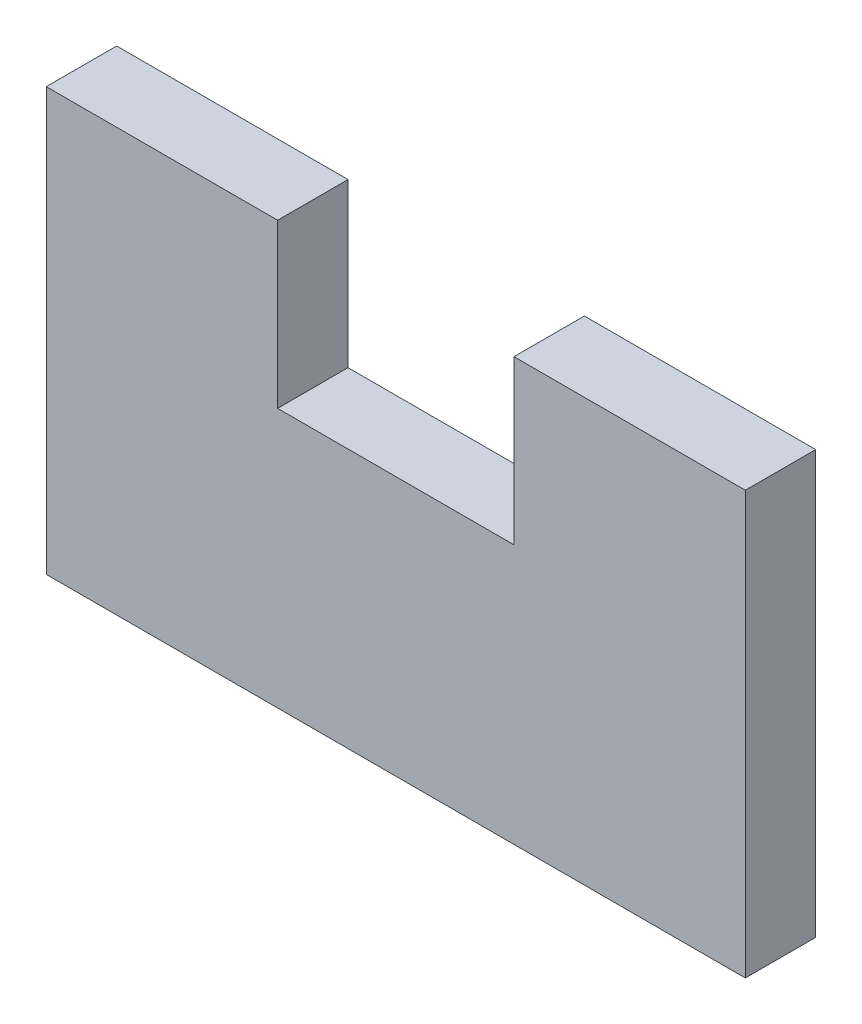
SolidWorks part; units mm, degrees
ref_plane "Front Plane" through (0, 0, 0) normal (0, 0, 1) x (1, 0, 0)
ref_plane "Top Plane" through (0, 0, 0) normal (0, 1, 0) x (1, 0, 0)
ref_plane "Right Plane" through (0, 0, 0) normal (1, 0, 0) x (0, 0, -1)
sketch "Sketch1" plane through (0, 0, 0) normal (0, 0, 1) x (1, 0, 0)
  line L0 (38.1765, 19.1703) -> (61.1765, 19.1703)
  line L1 (61.1765, 19.1703) -> (61.1765, -22.8297)
  line L2 (61.1765, -22.8297) -> (-8.3235, -22.8297)
  line L3 (-8.3235, -22.8297) -> (-8.3235, 19.1703)
  line L4 (-8.3235, 19.1703) -> (14.6765, 19.1703)
  line L6 (14.6765, 19.1703) -> (14.6765, 2.9703)
  line L7 (14.6765, 2.9703) -> (38.1765, 2.9703)
  line L8 (38.1765, 2.9703) -> (38.1765, 19.1703)
  dimension "D1" = 23
  dimension "D2" = 23
  dimension "D3" = 23.5
  dimension "D4" = 16.2
  dimension "D5" = 42
extrude "Boss-Extrude1" add sketch "Sketch1" along normal blind 7 contours L2 L3 L4 L6 L7 L8 L0 L1
sketch "Sketch2" plane through (0, 0, 7) normal (0, 0, 1) x (1, 0, 0)
  line L5 (-8.3235, 19.1703) -> (14.6765, 19.1703) construction
  line B0 (-8.3628, 5.3703) -> (-0.6392, 5.3703)
  line B1 (0.0096, 5.4413) -> (5.0778, 6.5639)
  line B2 (-8.3628, 2.8703) -> (-2.7898, 2.8703)
  line B3 (-0.8383, 2.1489) -> (3.0164, -1.1525)
  line B4 (-8.3628, 5.3703) -> (-8.3628, 2.8703)
  circle B5 centre (6.0509, 2.1703) radius 3
  arc B6 (3.0164, -1.1525) -> (5.0778, 6.5639) centre (6.0509, 2.1703) ccw
  arc B7 (-0.6392, 5.3703) -> (0.0096, 5.4413) centre (-0.6392, 8.3703) ccw
  arc B8 (-2.7898, 2.8703) -> (-0.8383, 2.1489) centre (-2.7898, -0.1297) cw
  dimension "D1" = 17
sketch_block_instance "Block1-1"
sketch_block "Block1" parameters "D1"=3
